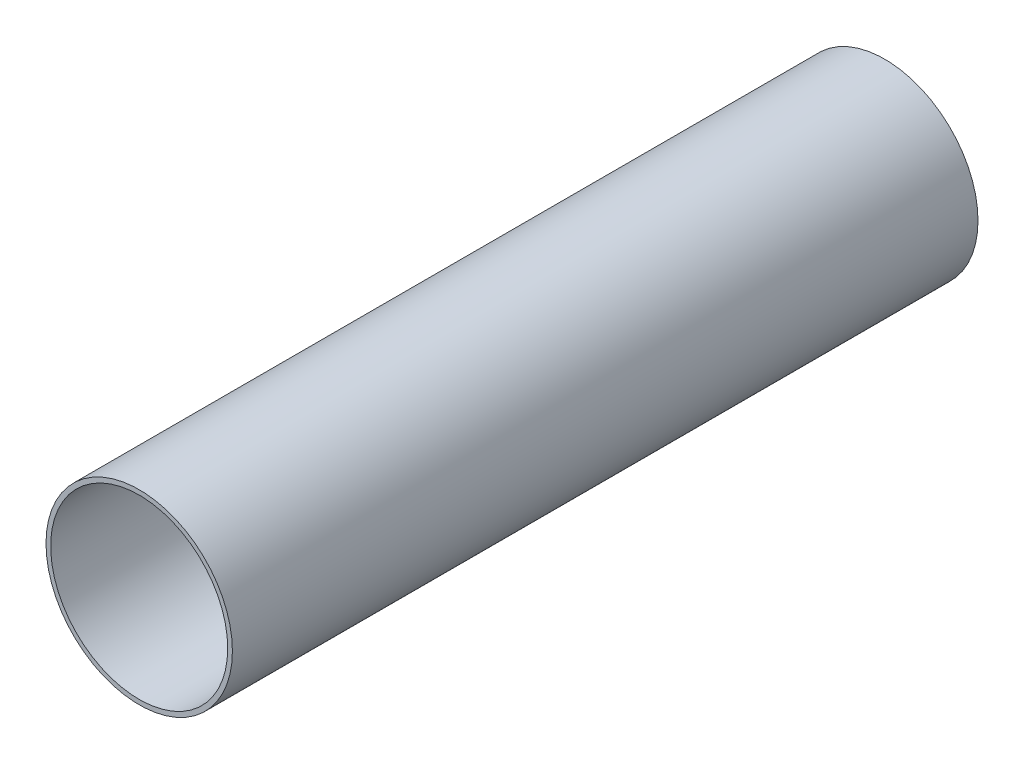
SolidWorks part; units mm, degrees
ref_plane "Front Plane" through (0, 0, 0) normal (0, 0, 1) x (1, 0, 0)
ref_plane "Top Plane" through (0, 0, 0) normal (0, 1, 0) x (1, 0, 0)
ref_plane "Right Plane" through (0, 0, 0) normal (1, 0, 0) x (0, 0, -1)
sketch "Sketch1" plane through (0, 0, 0) normal (0, 0, 1) x (1, 0, 0)
  circle A0 centre (0, 0) radius 63.5
  circle A1 centre (0, 0) radius 60.325
  dimension "D1" = 127
  dimension "D2" = 120.65
extrude "Boss-Extrude1" add sketch "Sketch1" against normal blind 508
